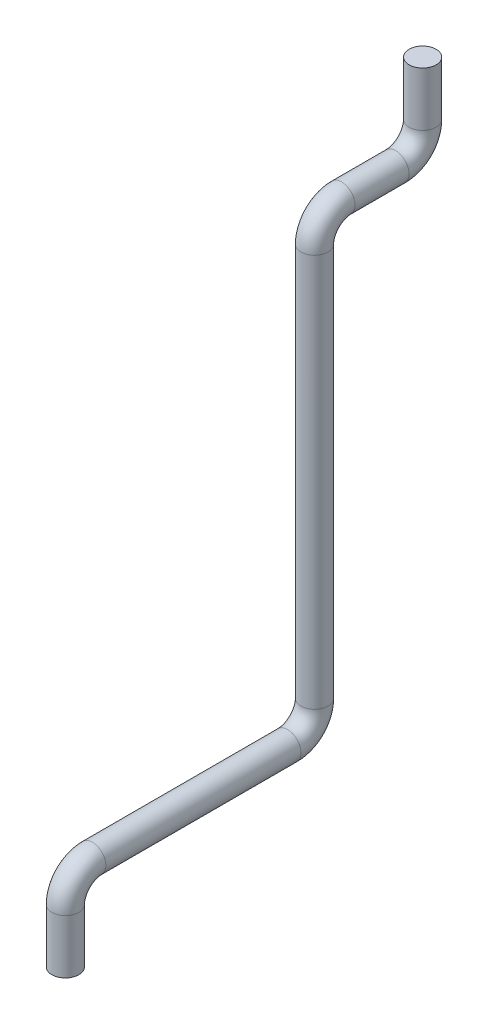
SolidWorks part; units mm, degrees
ref_plane "Front Plane" through (0, 0, 0) normal (0, 0, 1) x (1, 0, 0)
ref_plane "Top Plane" through (0, 0, 0) normal (0, 1, 0) x (1, 0, 0)
ref_plane "Right Plane" through (0, 0, 0) normal (1, 0, 0) x (0, 0, -1)
sketch "Sketch1" plane through (0, 0, 0) normal (1, 0, 0) x (0, 0, -1)
  line L0 (0, 0) -> (0, 2)
  line L1 (1, 3) -> (8.22, 3)
  line L2 (9.22, 4) -> (9.22, 18.55)
  line L3 (10.22, 19.55) -> (12.22, 19.55)
  line L4 (13.22, 20.55) -> (13.22, 22.55)
  arc A1 (0, 2) -> (1, 3) centre (1, 2) cw
  arc A2 (8.22, 3) -> (9.22, 4) centre (8.22, 4) ccw
  arc A3 (9.22, 18.55) -> (10.22, 19.55) centre (10.22, 18.55) cw
  arc A4 (12.22, 19.55) -> (13.22, 20.55) centre (12.22, 20.55) ccw
  point P13 (0, 3)
  point P16 (9.22, 3)
  point P19 (9.22, 19.55)
  point P22 (13.22, 19.55)
  dimension "D6" = 1
  dimension "D7" = 1
  dimension "D8" = 1
  dimension "D9" = 1
  dimension "D1" = 3
  dimension "D2" = 4
  dimension "D3" = 16.55
  dimension "D4" = 9.22
  dimension "D5" = 3
ref_plane "Plane1" through (0, 0, 0) normal (0, 1, 0) x (1, 0, 0)
sketch "Sketch2" plane through (0, 0, 0) normal (0, 1, 0) x (1, 0, 0)
  circle A0 centre (0, 0) radius 0.5
  dimension "D1" = 1
sweep "Sweep1" add profiles "Sketch2" path "Sketch1"
